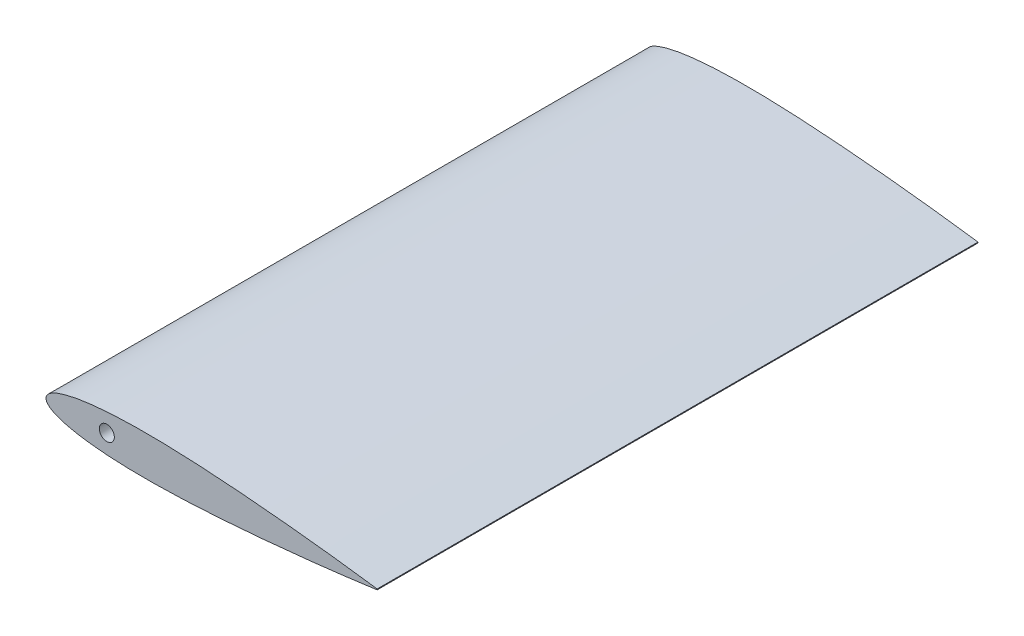
SolidWorks part; units mm, degrees
material "ABS"
ref_plane "Front Plane" through (0, 0, 0) normal (0, 0, 1) x (1, 0, 0)
ref_plane "Top Plane" through (0, 0, 0) normal (0, 1, 0) x (1, 0, 0)
ref_plane "Right Plane" through (0, 0, 0) normal (1, 0, 0) x (0, 0, -1)
curve "Curve1"
  spline degree 3 poles (1, 0.0013, 0) (0.9998, 0.0013, 0) (0.999, 0.0014, 0) (0.9973, 0.0016, 0) (0.9944, 0.002, 0) (0.9903, 0.0026, 0) (0.9851, 0.0033, 0) (0.9788, 0.0042, 0) (0.9713, 0.0052, 0) (0.9627, 0.0064, 0) (0.9531, 0.0077, 0) (0.9424, 0.0091, 0) (0.9307, 0.0106, 0) (0.9179, 0.0122, 0) (0.9042, 0.014, 0) (0.8895, 0.0158, 0) (0.874, 0.0177, 0) (0.8575, 0.0196, 0) (0.8402, 0.0217, 0) (0.8222, 0.0237, 0) (0.8033, 0.0259, 0) (0.7838, 0.028, 0) (0.7636, 0.0302, 0) (0.7428, 0.0324, 0) (0.7214, 0.0345, 0) (0.6995, 0.0367, 0) (0.6772, 0.0388, 0) (0.6544, 0.0409, 0) (0.6313, 0.043, 0) (0.6078, 0.045, 0) (0.5841, 0.0469, 0) (0.5602, 0.0488, 0) (0.5362, 0.0505, 0) (0.5121, 0.0522, 0) (0.4879, 0.0537, 0) (0.4638, 0.0551, 0) (0.4398, 0.0563, 0) (0.4159, 0.0574, 0) (0.3922, 0.0583, 0) (0.3688, 0.0591, 0) (0.3456, 0.0596, 0) (0.3228, 0.0599, 0) (0.3005, 0.0601, 0) (0.2786, 0.06, 0) (0.2572, 0.0596, 0) (0.2364, 0.0591, 0) (0.2162, 0.0583, 0) (0.1966, 0.0572, 0) (0.1778, 0.056, 0) (0.1597, 0.0544, 0) (0.1425, 0.0527, 0) (0.126, 0.0507, 0) (0.1104, 0.0486, 0) (0.0958, 0.0462, 0) (0.0821, 0.0436, 0) (0.0693, 0.0408, 0) (0.0576, 0.0378, 0) (0.0468, 0.0347, 0) (0.0372, 0.0313, 0) (0.0286, 0.0279, 0) (0.0211, 0.0243, 0) (0.0147, 0.0206, 0) (0.0094, 0.0167, 0) (0.0053, 0.0128, 0) (0.0023, 0.0087, 0) (0.0004, 0.0044, 0) (-0.0002, 0, 0) (0.0004, -0.0044, 0) (0.0023, -0.0087, 0) (0.0053, -0.0128, 0) (0.0094, -0.0167, 0) (0.0147, -0.0206, 0) (0.0211, -0.0243, 0) (0.0286, -0.0279, 0) (0.0372, -0.0313, 0) (0.0468, -0.0347, 0) (0.0576, -0.0378, 0) (0.0693, -0.0408, 0) (0.0821, -0.0436, 0) (0.0958, -0.0462, 0) (0.1104, -0.0486, 0) (0.126, -0.0507, 0) (0.1425, -0.0527, 0) (0.1597, -0.0544, 0) (0.1778, -0.056, 0) (0.1966, -0.0572, 0) (0.2162, -0.0583, 0) (0.2364, -0.0591, 0) (0.2572, -0.0596, 0) (0.2786, -0.06, 0) (0.3005, -0.0601, 0) (0.3228, -0.0599, 0) (0.3456, -0.0596, 0) (0.3688, -0.0591, 0) (0.3922, -0.0583, 0) (0.4159, -0.0574, 0) (0.4398, -0.0563, 0) (0.4638, -0.0551, 0) (0.4879, -0.0537, 0) (0.5121, -0.0522, 0) (0.5362, -0.0505, 0) (0.5602, -0.0488, 0) (0.5841, -0.0469, 0) (0.6078, -0.045, 0) (0.6313, -0.043, 0) (0.6544, -0.0409, 0) (0.6772, -0.0388, 0) (0.6995, -0.0367, 0) (0.7214, -0.0345, 0) (0.7428, -0.0324, 0) (0.7636, -0.0302, 0) (0.7838, -0.028, 0) (0.8033, -0.0259, 0) (0.8222, -0.0237, 0) (0.8402, -0.0217, 0) (0.8575, -0.0196, 0) (0.874, -0.0177, 0) (0.8895, -0.0158, 0) (0.9042, -0.014, 0) (0.9179, -0.0122, 0) (0.9307, -0.0106, 0) (0.9424, -0.0091, 0) (0.9531, -0.0077, 0) (0.9627, -0.0064, 0) (0.9713, -0.0052, 0) (0.9788, -0.0042, 0) (0.9851, -0.0033, 0) (0.9903, -0.0026, 0) (0.9944, -0.002, 0) (0.9973, -0.0016, 0) (0.999, -0.0014, 0) (0.9998, -0.0013, 0) (1, -0.0013, 0) knots 0 0 0 0 0.000289 0.001156 0.002598 0.004612 0.007194 0.010336 0.014031 0.018272 0.023046 0.028343 0.03415 0.040454 0.047238 0.054489 0.062187 0.070314 0.078852 0.08778 0.097078 0.106722 0.116691 0.126961 0.137507 0.148306 0.159331 0.170556 0.181957 0.193504 0.205171 0.216932 0.228758 0.240621 0.252495 0.26435 0.276161 0.287898 0.299536 0.311047 0.322405 0.333584 0.344559 0.355306 0.3658 0.376018 0.385937 0.395538 0.404798 0.413699 0.422221 0.430349 0.438066 0.445357 0.452209 0.458612 0.464554 0.47003 0.475035 0.479569 0.483637 0.48725 0.490431 0.493219 0.495674 0.497891 0.5 0.502109 0.504326 0.506781 0.509569 0.51275 0.516363 0.520431 0.524965 0.52997 0.535446 0.541388 0.547791 0.554643 0.561934 0.569651 0.577779 0.586301 0.595202 0.604462 0.614063 0.623982 0.6342 0.644694 0.655441 0.666416 0.677595 0.688953 0.700464 0.712102 0.723839 0.73565 0.747505 0.759379 0.771242 0.783068 0.794829 0.806496 0.818043 0.829444 0.840669 0.851694 0.862493 0.873039 0.883309 0.893278 0.902922 0.91222 0.921148 0.929686 0.937813 0.945511 0.952762 0.959546 0.96585 0.971657 0.976954 0.981728 0.985969 0.989664 0.992806 0.995388 0.997402 0.998844 0.999711 1 1 1 1
sketch "Sketch7" plane through (0, 0, 0) normal (0, 0, 1) x (1, 0, 0)
  line L0 (1, -0.1046) -> (1, 0.0066)
  spline S1 degree 3 poles (1, 0.0066) (0.1587, 0.1247) (-3.0116, 0.5533) (-7.4263, 1.0787) (-12.699, 1.6223) (-16.697, 1.9793) (-20.5193, 2.2595) (-23.6878, 2.4437) (-26.8012, 2.5658) (-29.7944, 2.6122) (-32.3272, 2.5764) (-34.3977, 2.4825) (-36.0221, 2.3618) (-37.507, 2.2006) (-38.649, 2.0297) (-39.4815, 1.872) (-40.0437, 1.7489) (-40.5616, 1.6177) (-41.0342, 1.4791) (-41.4602, 1.3334) (-41.8389, 1.1813) (-42.1694, 1.023) (-42.4512, 0.859) (-42.684, 0.6896) (-42.8671, 0.5144) (-43.0004, 0.333) (-43.0818, 0.1444) (-43.1089, -0.049) (-43.0818, -0.2425) (-43.0004, -0.431) (-42.8671, -0.6124) (-42.684, -0.7876) (-42.4512, -0.9571) (-42.1694, -1.121) (-41.8389, -1.2793) (-41.4602, -1.4315) (-41.0342, -1.5771) (-40.5616, -1.7158) (-40.0437, -1.8469) (-39.268, -2.0168) (-38.1929, -2.2036) (-36.7829, -2.3841) (-34.9303, -2.5522) (-32.6047, -2.6704) (-29.4493, -2.7151) (-26.1022, -2.6459) (-22.6345, -2.4865) (-19.4624, -2.2849) (-15.9943, -2.0156) (-12.9553, -1.7393) (-9.0386, -1.3466) (-5.1647, -0.9134) (-1.4665, -0.4436) (0.3805, -0.1913) (0.9229, -0.1154) (1, -0.1046) knots 0 0 0 0 0.028343 0.106722 0.148306 0.205171 0.240621 0.276161 0.311047 0.344559 0.376018 0.395538 0.413699 0.430349 0.445357 0.452209 0.458612 0.464554 0.47003 0.475035 0.479569 0.483637 0.48725 0.490431 0.493219 0.495674 0.497891 0.5 0.502109 0.504326 0.506781 0.509569 0.51275 0.516363 0.520431 0.524965 0.52997 0.535446 0.541388 0.547791 0.561934 0.577779 0.595202 0.623982 0.655441 0.700464 0.73565 0.771242 0.806496 0.851694 0.873039 0.937813 0.981728 0.997402 1 1 1 1
extrude "Boss-Extrude4" add sketch "Sketch7" along normal blind 80
sketch "Sketch8" plane through (0, 0, 80) normal (0, 0, 1) x (1, 0, 0)
  line L0 (1, -0.1046) -> (1, 0.0066) construction
  circle A0 centre (-35, 0) radius 1
  dimension "D1" = 36
extrude "Cut-Extrude3" cut sketch "Sketch8" against normal through all
